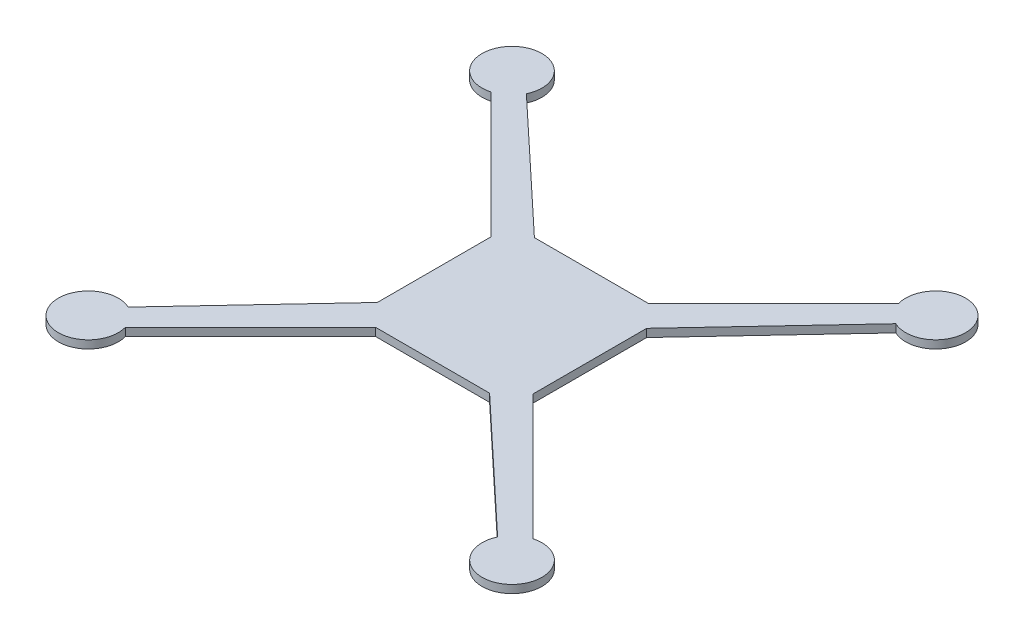
SolidWorks part; units mm, degrees
material "Hexcel AS4C (3000 丝)"
ref_plane "前视基准面" through (0, 0, 0) normal (0, 0, 1) x (1, 0, 0)
ref_plane "上视基准面" through (0, 0, 0) normal (0, 1, 0) x (1, 0, 0)
ref_plane "右视基准面" through (0, 0, 0) normal (1, 0, 0) x (0, 0, -1)
sketch "草图1" plane through (0, 0, 0) normal (0, 1, 0) x (1, 0, 0)
  line L0 (-49.4305, 0) -> (49.4305, 0) construction
  line L1 (0, 49.4305) -> (0, -49.4305) construction
  line L2 (-106.066, -106.066) -> (106.066, 106.066) construction
  line L3 (-106.066, 106.066) -> (106.066, -106.066) construction
  line L5 (28.1076, -39.3273) -> (-28.937, -39.3273)
  line L6 (39.3273, -28.937) -> (39.3273, 28.1076)
  line L7 (28.937, 39.3273) -> (-28.1076, 39.3273)
  line L8 (-39.3273, -28.1076) -> (-39.3273, 28.937)
  line L9 (40.0017, -40.9181) -> (-40.0017, 40.9181) construction
  line L10 (40.9181, 40.0017) -> (-40.9181, -40.0017) construction
  line L14 (-28.1076, 39.3273) -> (-92.489, 99.689)
  line L15 (-39.3273, 28.937) -> (-102.014, 91.6237)
  line L16 (28.937, 39.3273) -> (91.6237, 102.014)
  line L17 (39.3273, 28.1076) -> (99.689, 92.489)
  line L18 (39.3273, -28.937) -> (102.014, -91.6237)
  line L19 (28.1076, -39.3273) -> (92.489, -99.689)
  line L20 (-28.937, -39.3273) -> (-91.6237, -102.014)
  line L21 (-39.3273, -28.1076) -> (-99.689, -92.489)
  circle A0 centre (0, 0) radius 150 construction
  arc A13 (99.689, 92.489) -> (91.6237, 102.014) centre (106.066, 106.066) ccw
  arc A14 (92.489, -99.689) -> (102.014, -91.6237) centre (106.066, -106.066) ccw
  arc A15 (-99.689, -92.489) -> (-91.6237, -102.014) centre (-106.066, -106.066) ccw
  arc A16 (-92.489, 99.689) -> (-102.014, 91.6237) centre (-106.066, 106.066) ccw
  point P4 (0, 0)
  point P8 (0, 0)
  point P13 (0, 0)
  point P15 (0, 0)
  point P34 (0, 0)
  point P35 (0, 0)
  point P53 (0, 0)
  dimension "D2" = 300
  dimension "D3" = 30
  dimension "D4" = 39.3273
  dimension "D5" = 135
  dimension "D6" = 4
extrude "凸台-拉伸1" add sketch "草图1" along normal blind 4
